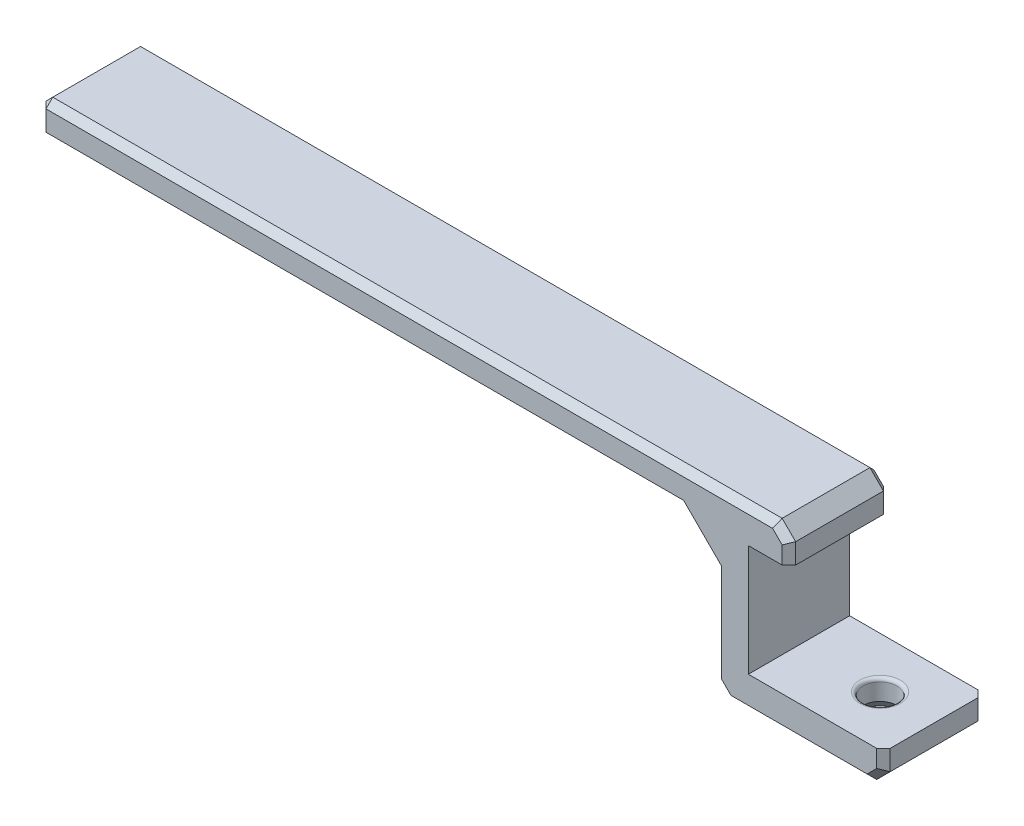
SolidWorks part; units mm, degrees
ref_plane "Plano frontal" through (0, 0, 0) normal (0, 0, 1) x (1, 0, 0)
ref_plane "Plano superior" through (0, 0, 0) normal (0, 1, 0) x (1, 0, 0)
ref_plane "Plano direito" through (0, 0, 0) normal (1, 0, 0) x (0, 0, -1)
sketch "Esboço1" plane through (0, 0, 0) normal (0, 0, 1) x (1, 0, 0)
  line L1 (0.2994, -0.75) -> (-5.7006, -0.75)
  line L3 (-5.7006, -17.25) -> (14.2994, -17.25)
  line L4 (14.2994, -17.25) -> (14.2994, -22.25)
  line L5 (14.2994, -22.25) -> (-10.7006, -22.25)
  line L7 (0.2994, 4.25) -> (0.2994, -0.75)
  line L9 (-5.7006, -0.75) -> (-5.7006, -17.25)
  line L15 (0.2994, 4.25) -> (-110.7006, 4.25)
  line L16 (-110.7006, 4.25) -> (-110.7006, -0.75)
  line L17 (-110.7006, -0.75) -> (-10.7006, -0.75)
  line L18 (-10.7006, -0.75) -> (-10.7006, -22.25)
  dimension "D1" = 5
  dimension "D2" = 20
  dimension "D3" = 16.5
  dimension "D4" = 6
  dimension "D5" = 5
  dimension "D6" = 100
  dimension "D7" = 5
  dimension "D8" = 5
extrude "Ressalto-extrusão1" add sketch "Esboço1" along normal blind 15
sketch "Esboço3" plane through (0, -22.25, 0) normal (0, -1, 0) x (1, 0, 0)
  line L0 (14.2994, 7.5) -> (6.2994, 7.5) construction
  line L1 (14.2994, 15) -> (14.2994, 0) construction
  circle A0 centre (6.2994, 7.5) radius 2.5
  dimension "D1" = 5
  dimension "D2" = 8
extrude "Corte-extrusão1" cut sketch "Esboço3" against normal blind 15
chamfer "Chanfro1" distance 2 angle 45 1 edges at (6.2994, -22.25, 5)
fillet "Filete1" radius 0.5 1 edges at (8.7994, -17.25, 7.5)
chamfer "Chanfro5" distance 2 angle 45 3 edges at (14.2994, -22.25, 7.5) (-10.7006, -22.25, 7.5) (0.2994, 4.25, 7.5)
chamfer "Chanfro7" distance 5 angle 45 1 edges at (-10.7006, -0.75, 7.5)
chamfer "Chanfro9" distance 1 angle 45 24 edges at (13.2994, -21.25, 0) (14.2994, -18.75, 0) (0.2994, 0.75, 0) (-0.7006, 3.25, 0) (-56.2006, 4.25, 0) (-110.7006, 1.75, 0) (-63.2006, -0.75, 0) (-13.2006, -3.25, 0) (-10.7006, -13, 0) (-9.7006, -21.25, 0) (1.7994, -22.25, 0) (-110.7006, 1.75, 15) (-56.2006, 4.25, 15) (-0.7006, 3.25, 15) (0.2994, 0.75, 15) (14.2994, -18.75, 15) (13.2994, -21.25, 15) (1.7994, -22.25, 15) (-9.7006, -21.25, 15) (-10.7006, -13, 15) (-13.2006, -3.25, 15) (-63.2006, -0.75, 15) (-110.7006, 4.25, 7.5) (-110.7006, -0.75, 7.5)
sketch "Esboço4" plane through (0, -10.75, 0) normal (0, 0, -1) x (1, 0, 0)
  line L3 (-104.9935, -12.5) -> (-19.9935, -12.5) construction
  line L4 (-104.9935, -11.6) -> (-19.9935, -11.6)
  line L5 (-104.9935, -13.4) -> (-19.9935, -13.4)
  line L6 (-15.2864, -11) -> (-15.2864, -14) construction
  line L7 (-2.1148, -14) -> (-109.7006, -14) construction
  line L8 (-15.2864, -12.5) -> (-109.7006, -12.5) construction
  line L9 (-109.7006, -14) -> (-109.7006, -11) construction
  arc A0 (-104.9935, -11.6) -> (-104.9935, -13.4) centre (-104.9935, -12.5) ccw
  arc A1 (-19.9935, -13.4) -> (-19.9935, -11.6) centre (-19.9935, -12.5) ccw
  point P0 (0, 0)
  point P1 (-62.4935, -12.5)
  point P8 (-62.4935, -12.5)
  point P23 (0, 0)
  dimension "D1" = 1.8
  dimension "D2" = 85
extrude "Corte-extrusão2" cut sketch "Esboço4" against normal blind 5
